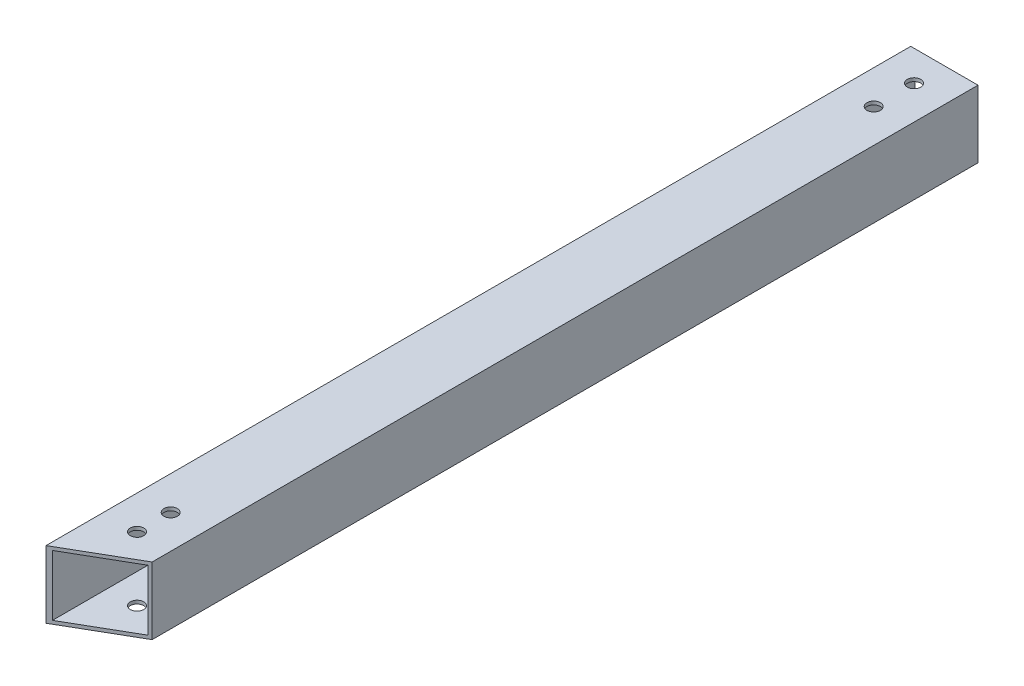
SolidWorks part; units mm, degrees
ref_plane "前视基准面" through (0, 0, 0) normal (0, 0, 1) x (1, 0, 0)
ref_plane "上视基准面" through (0, 0, 0) normal (0, 1, 0) x (1, 0, 0)
ref_plane "右视基准面" through (0, 0, 0) normal (1, 0, 0) x (0, 0, -1)
sketch "草图1" plane through (0, 0, 0) normal (0, 1, 0) x (1, 0, 0)
  line L0 (-10.2125, 128.5331) -> (9.7875, 128.5331)
  line L1 (9.7875, 128.5331) -> (9.7875, -116.9842)
  line L2 (9.7875, -116.9842) -> (-10.2125, -128.5312)
  line L3 (-10.2125, -128.5312) -> (-10.2125, 128.5331)
  circle A0 centre (-0.2125, -111.4669) radius 2
  circle A1 centre (-0.2125, -101.4669) radius 2
  circle A2 centre (-0.2125, 107.5331) radius 2
  circle A3 centre (-0.2125, 119.5331) radius 2
  dimension "D1" = 4
  dimension "D2" = 4
  dimension "D3" = 4
extrude "凸台-拉伸1" add sketch "草图1" along normal blind 20
sketch "草图2" plane through (0, 0, -128.5331) normal (0, 0, -1) x (-1, 0, 0)
  line L0 (0, 0) -> (0, 20) construction
  line L1 (-9.7875, 20) -> (10.2125, 20) construction
  line L3 (-9, 19) -> (9, 19)
  line L4 (-9, 19) -> (-9, 1)
  line L5 (-9, 1) -> (9, 1)
  line L6 (9, 19) -> (9, 1)
  line L7 (0, 1) -> (0, 19) construction
  line L8 (-9, 10) -> (9, 10) construction
  point P5 (0, 10)
  dimension "D1" = 18
  dimension "D2" = 18
extrude "切除-拉伸1" cut sketch "草图2" against normal through all
